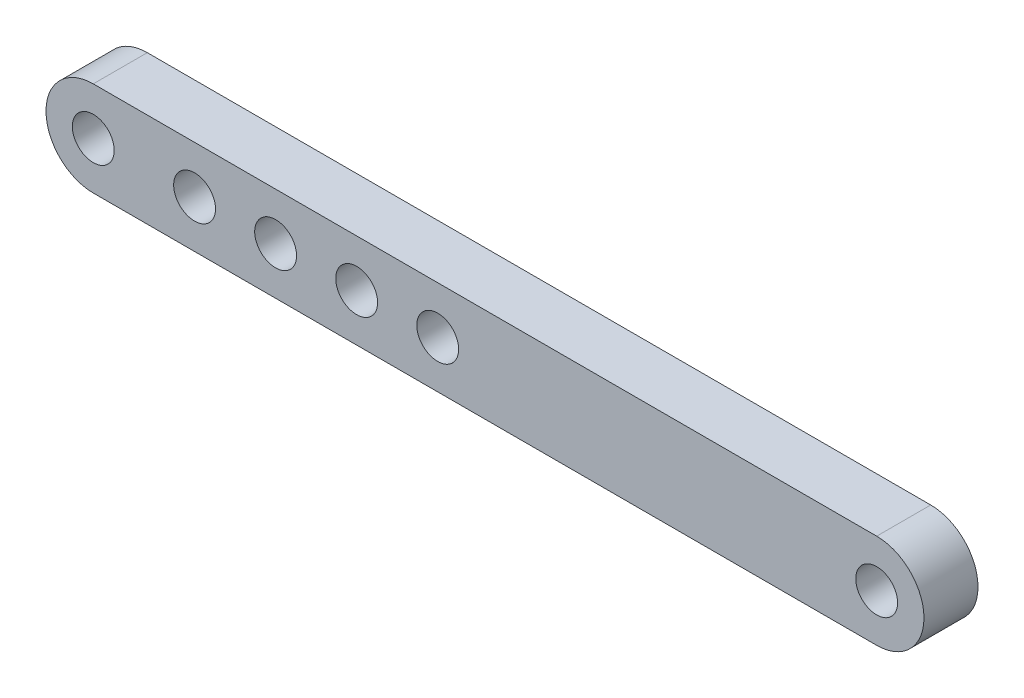
SolidWorks part; units mm, degrees
ref_plane "Front Plane" through (0, 0, 0) normal (0, 0, 1) x (1, 0, 0)
ref_plane "Top Plane" through (0, 0, 0) normal (0, 1, 0) x (1, 0, 0)
ref_plane "Right Plane" through (0, 0, 0) normal (1, 0, 0) x (0, 0, -1)
sketch "Sketch1" plane through (0, 0, 0) normal (0, 0, 1) x (1, 0, 0)
  line L0 (-33.3096, 0) -> (24.6904, 0) construction
  line L1 (-33.3096, 3.5) -> (24.6904, 3.5)
  line L2 (-33.3096, -3.5) -> (24.6904, -3.5)
  arc A0 (-33.3096, 3.5) -> (-33.3096, -3.5) centre (-33.3096, 0) ccw
  arc A1 (24.6904, -3.5) -> (24.6904, 3.5) centre (24.6904, 0) ccw
  point P3 (-4.3096, 0)
  point P8 (-36.8096, 0)
  point P9 (28.1904, 0)
  dimension "D1" = 65
  dimension "D2" = 7
extrude "Boss-Extrude1" add sketch "Sketch1" along normal blind 4
sketch "Sketch2" plane through (0, 0, 0) normal (0, 0, 1) x (1, 0, 0)
  circle A0 centre (-33.3096, 0) radius 1.55
  circle A1 centre (-19.8096, 0) radius 1.55
  circle A2 centre (24.6904, 0) radius 1.55
  arc A3 (-33.3096, 3.5) -> (-33.3096, -3.5) centre (-33.3096, 0) ccw construction
  circle A4 centre (-25.8096, 0) radius 1.55
  circle A5 centre (-13.8096, 0) radius 1.55
  circle A6 centre (-7.8096, 0) radius 1.55
  point P13 (-36.8096, 0)
  point P18 (0, 0)
  dimension "D1" = 3.1
  dimension "D2" = 3.1
  dimension "D3" = 3.1
  dimension "D6" = 3.1
  dimension "D7" = 3.1
  dimension "D8" = 3.1
  dimension "D4" = 11
  dimension "D5" = 3.5
  dimension "D9" = 6
  dimension "D10" = 6
  dimension "D11" = 6
extrude "Cut-Extrude6" cut sketch "Sketch2" along normal through all
equation "\"ScrewSize\"= 3.1mm"
